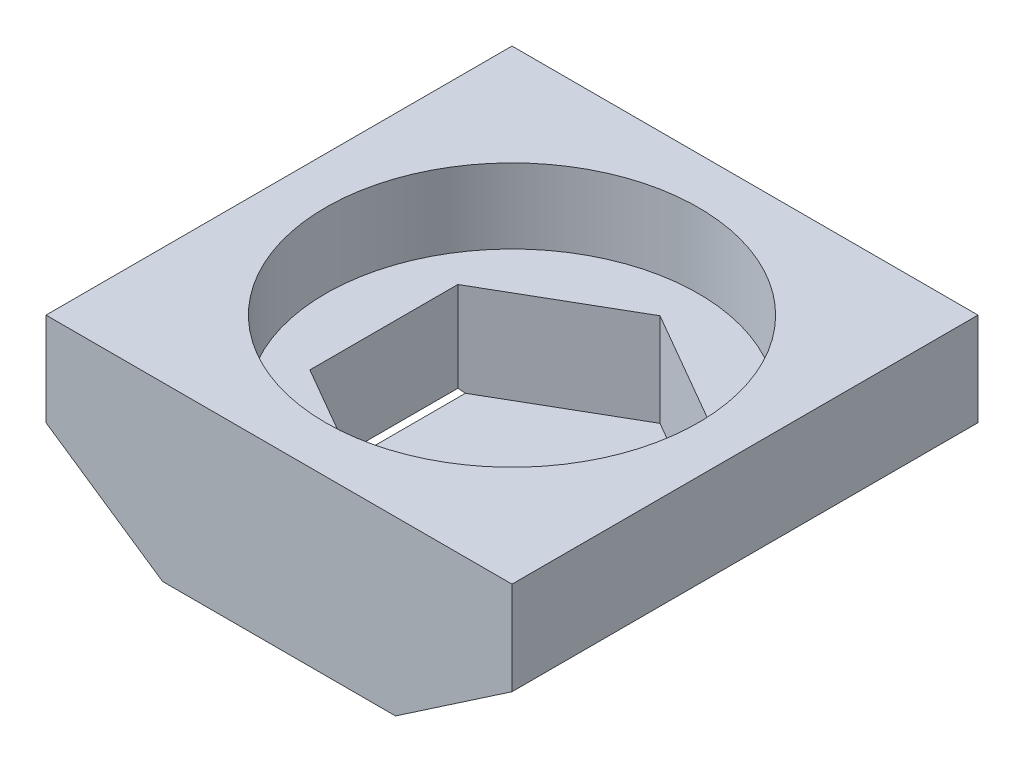
SolidWorks part; units mm, degrees
ref_plane "Спереди" through (0, 0, 0) normal (0, 0, 1) x (1, 0, 0)
ref_plane "Сверху" through (0, 0, 0) normal (0, 1, 0) x (1, 0, 0)
ref_plane "Справа" through (0, 0, 0) normal (1, 0, 0) x (0, 0, -1)
sketch "Эскиз1" plane through (0, 0, 0) normal (0, 0, 1) x (1, 0, 0)
  line L0 (0, 0) -> (0, 5.5988) construction
  line L1 (2.5, 0) -> (-2.5, 0)
  line L2 (-2.5, 0) -> (-5, 1.7)
  line L3 (-5, 1.7) -> (-5, 3.7)
  line L4 (-5, 3.7) -> (5, 3.7)
  line L5 (5, 1.7) -> (5, 3.7)
  line L6 (2.5, 0) -> (5, 1.7)
  point P8 (0, 3.7)
  dimension "D1" = 5
  dimension "D2" = 10
  dimension "D3" = 3.7
  dimension "D4" = 2
extrude "Бобышка-Вытянуть1" add sketch "Эскиз1" along normal blind 10
sketch "Эскиз2" plane through (0, 3.7, 0) normal (0, 1, 0) x (1, 0, 0)
  line L0 (0, 0) -> (0, -5) construction
  line L1 (2.75, -6.5877) -> (2.75, -3.4123)
  line L2 (2.75, -3.4123) -> (0, -1.8246)
  line L3 (0, -1.8246) -> (-2.75, -3.4123)
  line L4 (-2.75, -3.4123) -> (-2.75, -6.5877)
  line L5 (-2.75, -6.5877) -> (0, -8.1754)
  line L6 (0, -8.1754) -> (2.75, -6.5877)
  line L7 (5, 0) -> (-5, 0) construction
  line L8 (0, -5) -> (-5, -5) construction
  line L9 (-5, -10) -> (-5, 0) construction
  circle A0 centre (0, -5) radius 2.75 construction
  dimension "D1" = 5.5
extrude "Вырез-Вытянуть1" cut sketch "Эскиз2" against normal blind 3.6
sketch "Эскиз3" plane through (0, 3.7, 0) normal (0, 1, 0) x (1, 0, 0)
  line L0 (-2.75, -5) -> (2.75, -5) construction
  line L1 (-2.75, -3.4123) -> (-2.75, -6.5877) construction
  line L2 (2.75, -6.5877) -> (2.75, -3.4123) construction
  line L3 (0, 0) -> (0, -8.1754) construction
  circle A0 centre (0, -5) radius 4
  point P10 (0, -5)
  dimension "D1" = 8
extrude "Вырез-Вытянуть2" cut sketch "Эскиз3" against normal blind 1.6
